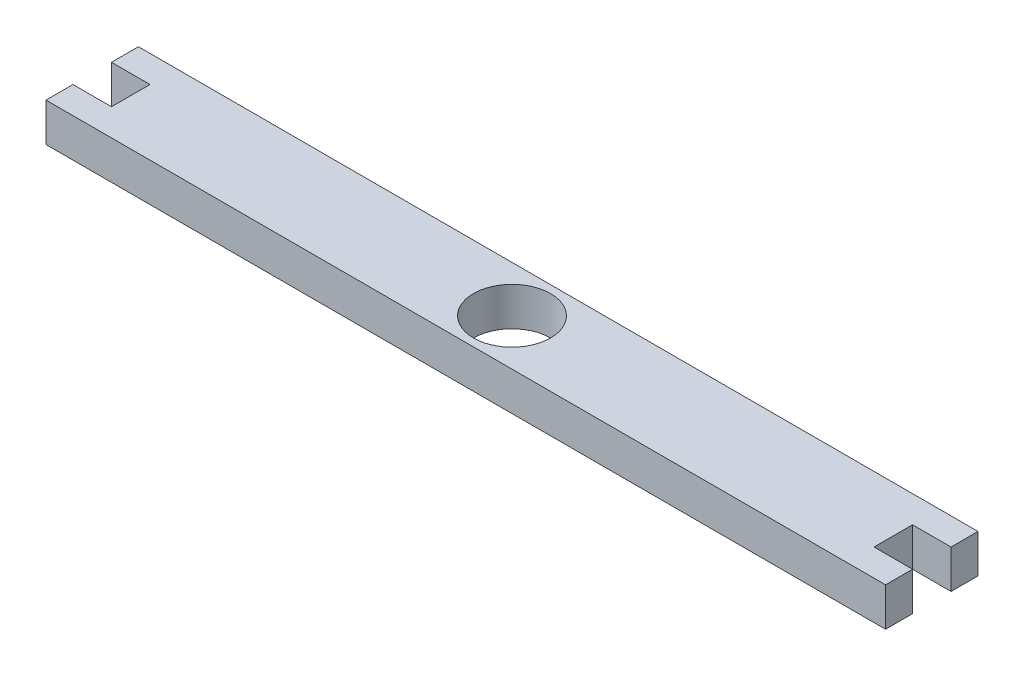
SolidWorks part; units mm, degrees
ref_plane "Front" through (0, 0, 0) normal (0, 0, 1) x (1, 0, 0)
ref_plane "Top" through (0, 0, 0) normal (0, 1, 0) x (1, 0, 0)
ref_plane "Right" through (0, 0, 0) normal (1, 0, 0) x (0, 0, -1)
sketch "Sketch1" plane through (0, 0, 0) normal (0, 1, 0) x (1, 0, 0)
  line L1 (-54.5, 6) -> (54.5, 6)
  line L2 (-54.5, 6) -> (-54.5, -6)
  line L3 (-54.5, -6) -> (54.5, -6)
  line L4 (54.5, 6) -> (54.5, -6)
  line L5 (-54.5, 6) -> (54.5, -6) construction
  line L6 (-54.5, -6) -> (54.5, 6) construction
  point P0 (0, 0)
  dimension "D1" = 12
  dimension "D2" = 109
extrude "Boss-Extrude1" add sketch "Sketch1" along normal blind 5
sketch "Sketch2" plane through (0, 5, 0) normal (0, 1, 0) x (1, 0, 0)
  circle A0 centre (0, 0) radius 5
  dimension "D1" = 10
extrude "Cut-Extrude2" cut sketch "Sketch2" against normal through all
sketch "Sketch3" plane through (0, 5, 0) normal (0, 1, 0) x (1, 0, 0)
  line L0 (-54.5, 0) -> (-54.5, 2.5)
  line L1 (-54.5, 6) -> (-54.5, -6) construction
  line L2 (-54.5, 2.5) -> (-49.5, 2.5)
  line L3 (-49.5, 2.5) -> (-49.5, -2.5)
  line L4 (-49.5, -2.5) -> (-54.5, -2.5)
  line L5 (-54.5, -2.5) -> (-54.5, 0)
  dimension "D1" = 2.5
  dimension "D2" = 2.5
  dimension "D3" = 5
extrude "Cut-Extrude3" cut sketch "Sketch3" against normal through all
mirror "Mirror1" about plane through (0, 0, 0) normal (1, 0, 0) of "Cut-Extrude3"
